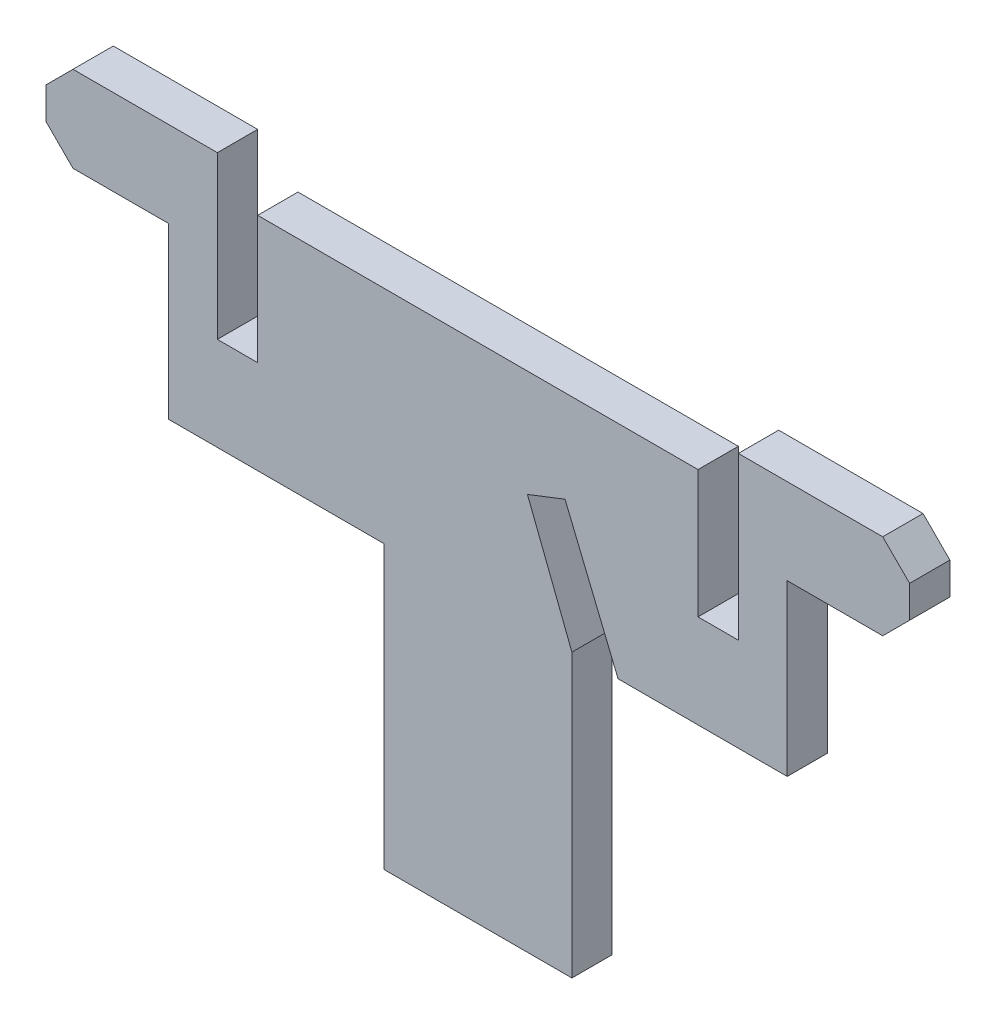
SolidWorks part; units mm, degrees
ref_plane "Front" through (0, 0, 0) normal (0, 0, 1) x (1, 0, 0)
ref_plane "Top" through (0, 0, 0) normal (0, 1, 0) x (1, 0, 0)
ref_plane "Right" through (0, 0, 0) normal (1, 0, 0) x (0, 0, -1)
sketch "Sketch1" plane through (0, 0, 0) normal (0, 0, 1) x (1, 0, 0)
  line L0 (507.3827, -79.1638) -> (509.3827, -81.1638)
  line L1 (509.3827, -83.5461) -> (507.3827, -85.5461)
  line L2 (457.8681, -79.1638) -> (447.1235, -79.1638)
  line L3 (460.8681, -91.199) -> (457.8681, -91.199)
  line L4 (454.2294, -98.164) -> (470.2531, -98.164)
  line L5 (484.2531, -119.164) -> (484.2531, -98.164)
  line L6 (454.2294, -98.164) -> (454.2294, -85.5461)
  line L7 (454.2294, -85.5461) -> (447.1235, -85.5461)
  line L8 (483.7406, -88.5649) -> (480.9444, -89.6517)
  line L9 (457.8681, -91.199) -> (457.8681, -79.1638)
  line L10 (460.8681, -81.7032) -> (460.8681, -91.199)
  line L11 (445.1235, -81.1638) -> (445.1235, -83.5461)
  line L13 (487.6863, -98.164) -> (483.7406, -88.5649)
  line L15 (480.9444, -89.6517) -> (484.2531, -98.164)
  line L16 (470.2531, -119.164) -> (484.2531, -119.164)
  line L18 (493.6381, -81.7032) -> (460.8681, -81.7032)
  line L19 (509.3827, -81.1638) -> (509.3827, -83.5461)
  line L20 (493.6381, -81.7032) -> (493.6381, -91.199)
  line L21 (496.6381, -91.199) -> (496.6381, -79.1638)
  line L22 (500.2768, -85.5461) -> (507.3827, -85.5461)
  line L23 (500.2768, -98.164) -> (500.2768, -85.5461)
  line L24 (500.2768, -98.164) -> (487.6863, -98.164)
  line L25 (493.6381, -91.199) -> (496.6381, -91.199)
  line L26 (470.2531, -119.164) -> (470.2531, -98.164)
  line L27 (496.6381, -79.1638) -> (507.3827, -79.1638)
  line L28 (445.1235, -83.5461) -> (447.1235, -85.5461)
  line L29 (477.2531, -81.7032) -> (477.2531, -119.164) construction
  line L30 (447.1235, -79.1638) -> (445.1235, -81.1638)
  point P2 (509.3827, -79.1638)
  point P3 (509.3827, -85.5461)
  point P34 (445.1235, -85.5461)
  point P35 (445.1235, -79.1638)
  dimension "D1" = 32.77
  dimension "D2" = 3
  dimension "D3" = 3
  dimension "D6" = 21
  dimension "D7" = 7
  dimension "D8" = 112.345
extrude "Base-Extrude" add sketch "Sketch1" along normal blind 3
